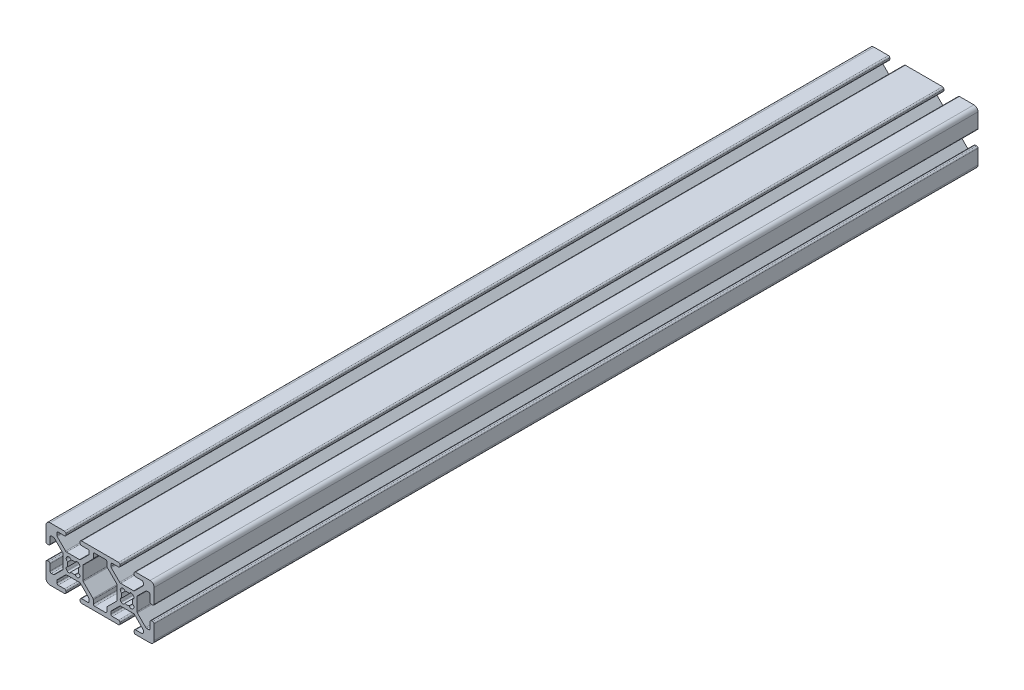
SolidWorks part; units mm, degrees
ref_plane "Front Plane" through (0, 0, 0) normal (0, 0, 1) x (1, 0, 0)
ref_plane "Top Plane" through (0, 0, 0) normal (0, 1, 0) x (1, 0, 0)
ref_plane "Right Plane" through (0, 0, 0) normal (1, 0, 0) x (0, 0, -1)
sketch "Sketch1" plane through (0, 0, 0) normal (0, 0, 1) x (1, 0, 0)
  line L0 (-16.6492, -61.9845) -> (-16.8288, -61.8049)
  line L1 (-16.8288, -57.5551) -> (-16.6492, -57.3755)
  line L2 (-12.3994, -57.3755) -> (-12.2198, -57.5551)
  line L3 (-12.2198, -61.8049) -> (-12.3994, -61.9845)
  line L4 (-27.0293, -67.672) -> (-27.0293, -66.3248)
  line L5 (-27.1781, -65.9655) -> (-30.7205, -62.4231)
  line L6 (-30.8693, -62.0639) -> (-30.8693, -57.2961)
  line L7 (-30.7205, -56.9369) -> (-27.1781, -53.3944)
  line L8 (-27.0293, -53.0352) -> (-27.0293, -51.688)
  line L9 (-26.5213, -51.18) -> (-22.5273, -51.18)
  line L10 (-22.0193, -51.688) -> (-22.0193, -53.0352)
  line L11 (-21.8705, -53.3944) -> (-18.3281, -56.9369)
  line L12 (-18.1793, -57.2961) -> (-18.1793, -62.0639)
  line L13 (-18.3281, -62.4231) -> (-21.8705, -65.9655)
  line L14 (-22.0193, -66.3248) -> (-22.0193, -67.672)
  line L15 (-22.5273, -68.18) -> (-26.5213, -68.18)
  line L16 (-36.6492, -61.9845) -> (-36.8288, -61.8049)
  line L17 (-36.8288, -57.5551) -> (-36.6492, -57.3755)
  line L18 (-32.3994, -57.3755) -> (-32.2198, -57.5551)
  line L19 (-32.2198, -61.8049) -> (-32.3994, -61.9845)
  line L20 (-36.9082, -63.335) -> (-32.1404, -63.335)
  line L21 (-31.7812, -63.4838) -> (-28.6781, -66.5869)
  line L22 (-28.5293, -66.9461) -> (-28.5293, -67.672)
  line L23 (-29.0373, -68.18) -> (-31.3863, -68.18)
  line L24 (-31.8943, -68.688) -> (-31.8943, -69.172)
  line L25 (-31.3863, -69.68) -> (-17.6623, -69.68)
  line L26 (-17.1543, -69.172) -> (-17.1543, -68.688)
  line L27 (-17.6623, -68.18) -> (-20.0113, -68.18)
  line L28 (-20.5193, -67.672) -> (-20.5193, -66.9461)
  line L29 (-20.3705, -66.5869) -> (-17.2674, -63.4838)
  line L30 (-16.9082, -63.335) -> (-12.1404, -63.335)
  line L31 (-11.7812, -63.4838) -> (-8.6781, -66.5869)
  line L32 (-8.5293, -66.9461) -> (-8.5293, -67.672)
  line L33 (-9.0373, -68.18) -> (-11.3863, -68.18)
  line L34 (-11.8943, -68.688) -> (-11.8943, -69.172)
  line L35 (-11.3863, -69.68) -> (-6.0243, -69.68)
  line L36 (-4.5243, -68.18) -> (-4.5243, -62.818)
  line L37 (-5.0323, -62.31) -> (-5.5163, -62.31)
  line L38 (-6.0243, -62.818) -> (-6.0243, -65.167)
  line L39 (-6.5323, -65.675) -> (-7.2582, -65.675)
  line L40 (-7.6174, -65.5262) -> (-10.7205, -62.4231)
  line L41 (-10.8693, -62.0639) -> (-10.8693, -57.2961)
  line L42 (-10.7205, -56.9369) -> (-7.6174, -53.8338)
  line L43 (-7.2582, -53.685) -> (-6.5323, -53.685)
  line L44 (-6.0243, -54.193) -> (-6.0243, -56.542)
  line L45 (-5.5163, -57.05) -> (-5.0323, -57.05)
  line L46 (-4.5243, -56.542) -> (-4.5243, -51.18)
  line L47 (-6.0243, -49.68) -> (-11.3863, -49.68)
  line L48 (-11.8943, -50.188) -> (-11.8943, -50.672)
  line L49 (-11.3863, -51.18) -> (-9.0373, -51.18)
  line L50 (-8.5293, -51.688) -> (-8.5293, -52.4139)
  line L51 (-8.6781, -52.7731) -> (-11.7812, -55.8762)
  line L52 (-12.1404, -56.025) -> (-16.9082, -56.025)
  line L53 (-17.2674, -55.8762) -> (-20.3705, -52.7731)
  line L54 (-20.5193, -52.4139) -> (-20.5193, -51.688)
  line L55 (-20.0113, -51.18) -> (-17.6623, -51.18)
  line L56 (-17.1543, -50.672) -> (-17.1543, -50.188)
  line L57 (-17.6623, -49.68) -> (-31.3863, -49.68)
  line L58 (-31.8943, -50.188) -> (-31.8943, -50.672)
  line L59 (-31.3863, -51.18) -> (-29.0373, -51.18)
  line L60 (-28.5293, -51.688) -> (-28.5293, -52.4139)
  line L61 (-28.6781, -52.7731) -> (-31.7812, -55.8762)
  line L62 (-32.1404, -56.025) -> (-36.9082, -56.025)
  line L63 (-37.2674, -55.8762) -> (-40.3705, -52.7731)
  line L64 (-40.5193, -52.4139) -> (-40.5193, -51.688)
  line L65 (-40.0113, -51.18) -> (-37.6623, -51.18)
  line L66 (-37.1543, -50.672) -> (-37.1543, -50.188)
  line L67 (-37.6623, -49.68) -> (-43.0243, -49.68)
  line L68 (-44.5243, -51.18) -> (-44.5243, -56.542)
  line L69 (-44.0163, -57.05) -> (-43.5323, -57.05)
  line L70 (-43.0243, -56.542) -> (-43.0243, -54.193)
  line L71 (-42.5163, -53.685) -> (-41.7904, -53.685)
  line L72 (-41.4312, -53.8338) -> (-38.3281, -56.9369)
  line L73 (-38.1793, -57.2961) -> (-38.1793, -62.0639)
  line L74 (-38.3281, -62.4231) -> (-41.4312, -65.5262)
  line L75 (-41.7904, -65.675) -> (-42.5163, -65.675)
  line L76 (-43.0243, -65.167) -> (-43.0243, -62.818)
  line L77 (-43.5323, -62.31) -> (-44.0163, -62.31)
  line L78 (-44.5243, -62.818) -> (-44.5243, -68.18)
  line L79 (-43.0243, -69.68) -> (-37.6623, -69.68)
  line L80 (-37.1543, -69.172) -> (-37.1543, -68.688)
  line L81 (-37.6623, -68.18) -> (-40.0113, -68.18)
  line L82 (-40.5193, -67.672) -> (-40.5193, -66.9461)
  line L83 (-40.3705, -66.5869) -> (-37.2674, -63.4838)
  arc A0 (-16.4594, -60.484) -> (-16.8288, -61.8049) centre (-16.2723, -61.2484) ccw
  arc A1 (-16.4594, -58.876) -> (-16.4594, -60.484) centre (-14.5243, -59.68) ccw
  arc A2 (-16.8288, -57.5551) -> (-16.4594, -58.876) centre (-16.2723, -58.1116) ccw
  arc A3 (-15.3283, -57.7449) -> (-16.6492, -57.3755) centre (-16.0927, -57.932) ccw
  arc A4 (-13.7203, -57.7449) -> (-15.3283, -57.7449) centre (-14.5243, -59.68) ccw
  arc A5 (-12.3994, -57.3755) -> (-13.7203, -57.7449) centre (-12.9559, -57.932) ccw
  arc A6 (-12.5892, -58.876) -> (-12.2198, -57.5551) centre (-12.7763, -58.1116) ccw
  arc A7 (-12.5892, -60.484) -> (-12.5892, -58.876) centre (-14.5243, -59.68) ccw
  arc A8 (-12.2198, -61.8049) -> (-12.5892, -60.484) centre (-12.7763, -61.2484) ccw
  arc A9 (-13.7203, -61.6151) -> (-12.3994, -61.9845) centre (-12.9559, -61.428) ccw
  arc A10 (-15.3283, -61.6151) -> (-13.7203, -61.6151) centre (-14.5243, -59.68) ccw
  arc A11 (-16.6492, -61.9845) -> (-15.3283, -61.6151) centre (-16.0927, -61.428) ccw
  arc A12 (-27.0293, -67.672) -> (-26.5213, -68.18) centre (-26.5213, -67.672) ccw
  arc A13 (-27.0293, -66.3248) -> (-27.1781, -65.9655) centre (-27.5373, -66.3248) ccw
  arc A14 (-30.8693, -62.0639) -> (-30.7205, -62.4231) centre (-30.3613, -62.0639) ccw
  arc A15 (-30.7205, -56.9369) -> (-30.8693, -57.2961) centre (-30.3613, -57.2961) ccw
  arc A16 (-27.1781, -53.3944) -> (-27.0293, -53.0352) centre (-27.5373, -53.0352) ccw
  arc A17 (-26.5213, -51.18) -> (-27.0293, -51.688) centre (-26.5213, -51.688) ccw
  arc A18 (-22.0193, -51.688) -> (-22.5273, -51.18) centre (-22.5273, -51.688) ccw
  arc A19 (-22.0193, -53.0352) -> (-21.8705, -53.3944) centre (-21.5113, -53.0352) ccw
  arc A20 (-18.1793, -57.2961) -> (-18.3281, -56.9369) centre (-18.6873, -57.2961) ccw
  arc A21 (-18.3281, -62.4231) -> (-18.1793, -62.0639) centre (-18.6873, -62.0639) ccw
  arc A22 (-21.8705, -65.9655) -> (-22.0193, -66.3248) centre (-21.5113, -66.3248) ccw
  arc A23 (-22.5273, -68.18) -> (-22.0193, -67.672) centre (-22.5273, -67.672) ccw
  arc A24 (-36.4594, -60.484) -> (-36.8288, -61.8049) centre (-36.2723, -61.2484) ccw
  arc A25 (-36.4594, -58.876) -> (-36.4594, -60.484) centre (-34.5243, -59.68) ccw
  arc A26 (-36.8288, -57.5551) -> (-36.4594, -58.876) centre (-36.2723, -58.1116) ccw
  arc A27 (-35.3283, -57.7449) -> (-36.6492, -57.3755) centre (-36.0927, -57.932) ccw
  arc A28 (-33.7203, -57.7449) -> (-35.3283, -57.7449) centre (-34.5243, -59.68) ccw
  arc A29 (-32.3994, -57.3755) -> (-33.7203, -57.7449) centre (-32.9559, -57.932) ccw
  arc A30 (-32.5892, -58.876) -> (-32.2198, -57.5551) centre (-32.7763, -58.1116) ccw
  arc A31 (-32.5892, -60.484) -> (-32.5892, -58.876) centre (-34.5243, -59.68) ccw
  arc A32 (-32.2198, -61.8049) -> (-32.5892, -60.484) centre (-32.7763, -61.2484) ccw
  arc A33 (-33.7203, -61.6151) -> (-32.3994, -61.9845) centre (-32.9559, -61.428) ccw
  arc A34 (-35.3283, -61.6151) -> (-33.7203, -61.6151) centre (-34.5243, -59.68) ccw
  arc A35 (-36.6492, -61.9845) -> (-35.3283, -61.6151) centre (-36.0927, -61.428) ccw
  arc A36 (-36.9082, -63.335) -> (-37.2674, -63.4838) centre (-36.9082, -63.843) ccw
  arc A37 (-31.7812, -63.4838) -> (-32.1404, -63.335) centre (-32.1404, -63.843) ccw
  arc A38 (-28.5293, -66.9461) -> (-28.6781, -66.5869) centre (-29.0373, -66.9461) ccw
  arc A39 (-29.0373, -68.18) -> (-28.5293, -67.672) centre (-29.0373, -67.672) ccw
  arc A40 (-31.3863, -68.18) -> (-31.8943, -68.688) centre (-31.3863, -68.688) ccw
  arc A41 (-31.8943, -69.172) -> (-31.3863, -69.68) centre (-31.3863, -69.172) ccw
  arc A42 (-17.6623, -69.68) -> (-17.1543, -69.172) centre (-17.6623, -69.172) ccw
  arc A43 (-17.1543, -68.688) -> (-17.6623, -68.18) centre (-17.6623, -68.688) ccw
  arc A44 (-20.5193, -67.672) -> (-20.0113, -68.18) centre (-20.0113, -67.672) ccw
  arc A45 (-20.3705, -66.5869) -> (-20.5193, -66.9461) centre (-20.0113, -66.9461) ccw
  arc A46 (-16.9082, -63.335) -> (-17.2674, -63.4838) centre (-16.9082, -63.843) ccw
  arc A47 (-11.7812, -63.4838) -> (-12.1404, -63.335) centre (-12.1404, -63.843) ccw
  arc A48 (-8.5293, -66.9461) -> (-8.6781, -66.5869) centre (-9.0373, -66.9461) ccw
  arc A49 (-9.0373, -68.18) -> (-8.5293, -67.672) centre (-9.0373, -67.672) ccw
  arc A50 (-11.3863, -68.18) -> (-11.8943, -68.688) centre (-11.3863, -68.688) ccw
  arc A51 (-11.8943, -69.172) -> (-11.3863, -69.68) centre (-11.3863, -69.172) ccw
  arc A52 (-6.0243, -69.68) -> (-4.5243, -68.18) centre (-6.0243, -68.18) ccw
  arc A53 (-4.5243, -62.818) -> (-5.0323, -62.31) centre (-5.0323, -62.818) ccw
  arc A54 (-5.5163, -62.31) -> (-6.0243, -62.818) centre (-5.5163, -62.818) ccw
  arc A55 (-6.5323, -65.675) -> (-6.0243, -65.167) centre (-6.5323, -65.167) ccw
  arc A56 (-7.6174, -65.5262) -> (-7.2582, -65.675) centre (-7.2582, -65.167) ccw
  arc A57 (-10.8693, -62.0639) -> (-10.7205, -62.4231) centre (-10.3613, -62.0639) ccw
  arc A58 (-10.7205, -56.9369) -> (-10.8693, -57.2961) centre (-10.3613, -57.2961) ccw
  arc A59 (-7.2582, -53.685) -> (-7.6174, -53.8338) centre (-7.2582, -54.193) ccw
  arc A60 (-6.0243, -54.193) -> (-6.5323, -53.685) centre (-6.5323, -54.193) ccw
  arc A61 (-6.0243, -56.542) -> (-5.5163, -57.05) centre (-5.5163, -56.542) ccw
  arc A62 (-5.0323, -57.05) -> (-4.5243, -56.542) centre (-5.0323, -56.542) ccw
  arc A63 (-4.5243, -51.18) -> (-6.0243, -49.68) centre (-6.0243, -51.18) ccw
  arc A64 (-11.3863, -49.68) -> (-11.8943, -50.188) centre (-11.3863, -50.188) ccw
  arc A65 (-11.8943, -50.672) -> (-11.3863, -51.18) centre (-11.3863, -50.672) ccw
  arc A66 (-8.5293, -51.688) -> (-9.0373, -51.18) centre (-9.0373, -51.688) ccw
  arc A67 (-8.6781, -52.7731) -> (-8.5293, -52.4139) centre (-9.0373, -52.4139) ccw
  arc A68 (-12.1404, -56.025) -> (-11.7812, -55.8762) centre (-12.1404, -55.517) ccw
  arc A69 (-17.2674, -55.8762) -> (-16.9082, -56.025) centre (-16.9082, -55.517) ccw
  arc A70 (-20.5193, -52.4139) -> (-20.3705, -52.7731) centre (-20.0113, -52.4139) ccw
  arc A71 (-20.0113, -51.18) -> (-20.5193, -51.688) centre (-20.0113, -51.688) ccw
  arc A72 (-17.6623, -51.18) -> (-17.1543, -50.672) centre (-17.6623, -50.672) ccw
  arc A73 (-17.1543, -50.188) -> (-17.6623, -49.68) centre (-17.6623, -50.188) ccw
  arc A74 (-31.3863, -49.68) -> (-31.8943, -50.188) centre (-31.3863, -50.188) ccw
  arc A75 (-31.8943, -50.672) -> (-31.3863, -51.18) centre (-31.3863, -50.672) ccw
  arc A76 (-28.5293, -51.688) -> (-29.0373, -51.18) centre (-29.0373, -51.688) ccw
  arc A77 (-28.6781, -52.7731) -> (-28.5293, -52.4139) centre (-29.0373, -52.4139) ccw
  arc A78 (-32.1404, -56.025) -> (-31.7812, -55.8762) centre (-32.1404, -55.517) ccw
  arc A79 (-37.2674, -55.8762) -> (-36.9082, -56.025) centre (-36.9082, -55.517) ccw
  arc A80 (-40.5193, -52.4139) -> (-40.3705, -52.7731) centre (-40.0113, -52.4139) ccw
  arc A81 (-40.0113, -51.18) -> (-40.5193, -51.688) centre (-40.0113, -51.688) ccw
  arc A82 (-37.6623, -51.18) -> (-37.1543, -50.672) centre (-37.6623, -50.672) ccw
  arc A83 (-37.1543, -50.188) -> (-37.6623, -49.68) centre (-37.6623, -50.188) ccw
  arc A84 (-43.0243, -49.68) -> (-44.5243, -51.18) centre (-43.0243, -51.18) ccw
  arc A85 (-44.5243, -56.542) -> (-44.0163, -57.05) centre (-44.0163, -56.542) ccw
  arc A86 (-43.5323, -57.05) -> (-43.0243, -56.542) centre (-43.5323, -56.542) ccw
  arc A87 (-42.5163, -53.685) -> (-43.0243, -54.193) centre (-42.5163, -54.193) ccw
  arc A88 (-41.4312, -53.8338) -> (-41.7904, -53.685) centre (-41.7904, -54.193) ccw
  arc A89 (-38.1793, -57.2961) -> (-38.3281, -56.9369) centre (-38.6873, -57.2961) ccw
  arc A90 (-38.3281, -62.4231) -> (-38.1793, -62.0639) centre (-38.6873, -62.0639) ccw
  arc A91 (-41.7904, -65.675) -> (-41.4312, -65.5262) centre (-41.7904, -65.167) ccw
  arc A92 (-43.0243, -65.167) -> (-42.5163, -65.675) centre (-42.5163, -65.167) ccw
  arc A93 (-43.0243, -62.818) -> (-43.5323, -62.31) centre (-43.5323, -62.818) ccw
  arc A94 (-44.0163, -62.31) -> (-44.5243, -62.818) centre (-44.0163, -62.818) ccw
  arc A95 (-44.5243, -68.18) -> (-43.0243, -69.68) centre (-43.0243, -68.18) ccw
  arc A96 (-37.6623, -69.68) -> (-37.1543, -69.172) centre (-37.6623, -69.172) ccw
  arc A97 (-37.1543, -68.688) -> (-37.6623, -68.18) centre (-37.6623, -68.688) ccw
  arc A98 (-40.5193, -67.672) -> (-40.0113, -68.18) centre (-40.0113, -67.672) ccw
  arc A99 (-40.3705, -66.5869) -> (-40.5193, -66.9461) centre (-40.0113, -66.9461) ccw
extrude "Extrude1" add sketch "Sketch1" along normal blind 304.8
